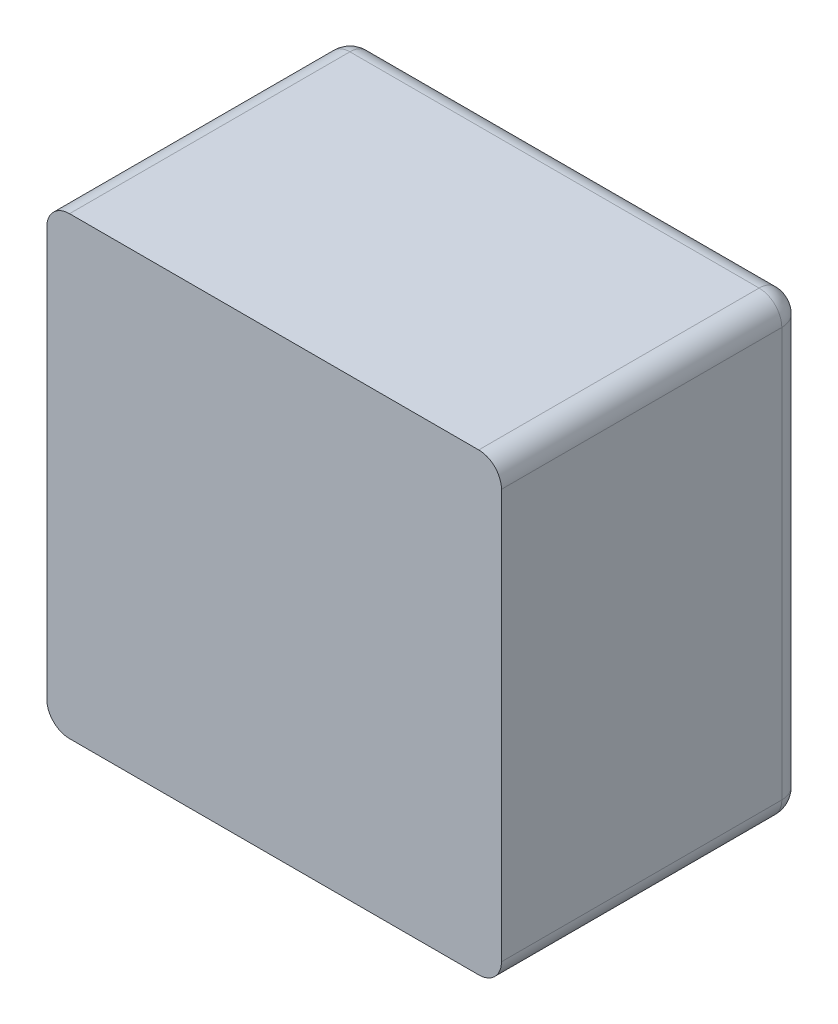
SolidWorks part; units mm, degrees
ref_plane "Front Plane" through (0, 0, 0) normal (0, 0, 1) x (1, 0, 0)
ref_plane "Top Plane" through (0, 0, 0) normal (0, 1, 0) x (1, 0, 0)
ref_plane "Right Plane" through (0, 0, 0) normal (1, 0, 0) x (0, 0, -1)
sketch "Sketch1" plane through (0, 0, 0) normal (0, 0, 1) x (1, 0, 0)
  line L1 (-25, 26.5625) -> (35, 26.5625)
  line L2 (-25, 26.5625) -> (-25, -33.4375)
  line L3 (-25, -33.4375) -> (35, -33.4375)
  line L4 (35, 26.5625) -> (35, -33.4375)
  dimension "D1" = 60
  dimension "D2" = 60
extrude "Boss-Extrude1" add sketch "Sketch1" along normal blind 40
fillet "Fillet1" radius 3 4 edges at (35, -33.4375, 20) (-25, -33.4375, 20) (-25, 26.5625, 20) (35, 26.5625, 20)
fillet "Fillet2" radius 3 8 edges at (34.1213, 25.6838, 0) (5, 26.5625, 0) (-24.1213, 25.6838, 0) (-25, -3.4375, 0) (-24.1213, -32.5588, 0) (5, -33.4375, 0) (34.1213, -32.5588, 0) (35, -3.4375, 0)
sketch "Sketch2" plane through (0, 0, 0) normal (0, 0, -1) x (-1, 0, 0)
  line L2 (25, 23.5625) -> (25, -30.4375) construction
  line L3 (-32, 26.5625) -> (22, 26.5625) construction
  circle A0 centre (-5, -3.4375) radius 20
  dimension "D1" = 40
  dimension "D2" = 30
  dimension "D3" = 30
extrude "Cut-Extrude1" cut sketch "Sketch2" against normal blind 1
